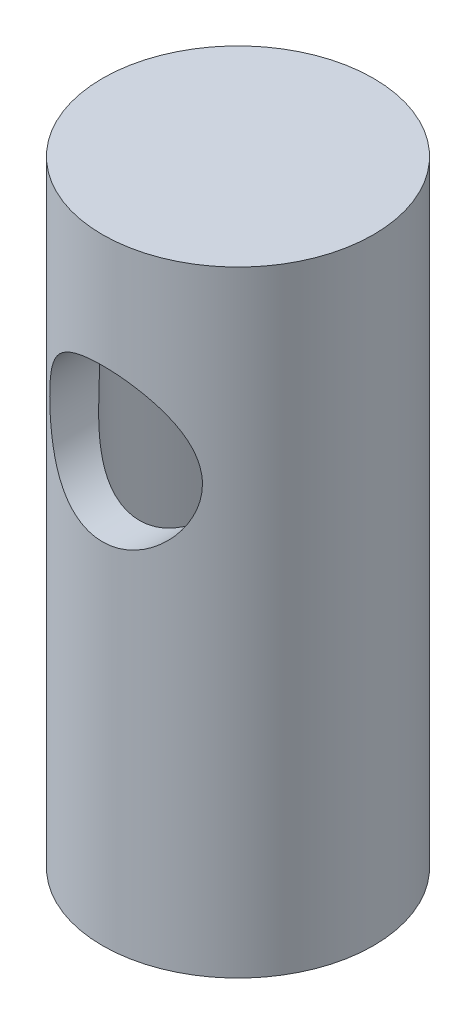
SolidWorks part; units mm, degrees
ref_plane "前视基准面" through (0, 0, 0) normal (0, 0, 1) x (1, 0, 0)
ref_plane "上视基准面" through (0, 0, 0) normal (0, 1, 0) x (1, 0, 0)
ref_plane "右视基准面" through (0, 0, 0) normal (1, 0, 0) x (0, 0, -1)
sketch "草图1" plane through (0, 0, 0) normal (0, 0, 1) x (1, 0, 0)
  line B0 (5.5, 25) -> (0, 25)
  line B1 (0, 25) -> (0, 0)
  line B2 (5.5, 25) -> (5.5, 0)
  line B3 (0, 0) -> (5.5, 0)
sketch_block_instance "A$C22D00606-1"
sketch_block "A$C22D00606"
revolve "旋转1" add sketch "草图1" angle 360 about L1
sketch "草图3" plane through (0, 0, 0) normal (0, 0, 1) x (1, 0, 0)
  line L0 (-5.5, 0) -> (5.5, 0) construction
  circle A0 centre (0, 17.3) radius 3.1
  dimension "D1" = 17.3
extrude "切除-拉伸1" cut sketch "草图3" against normal through all and the other way through all
sketch "草图4" plane through (0, 0, 0) normal (0, -1, 0) x (1, 0, 0)
  circle A0 centre (0, 0) radius 4
extrude "切除-拉伸2" cut sketch "草图4" against normal blind 24
